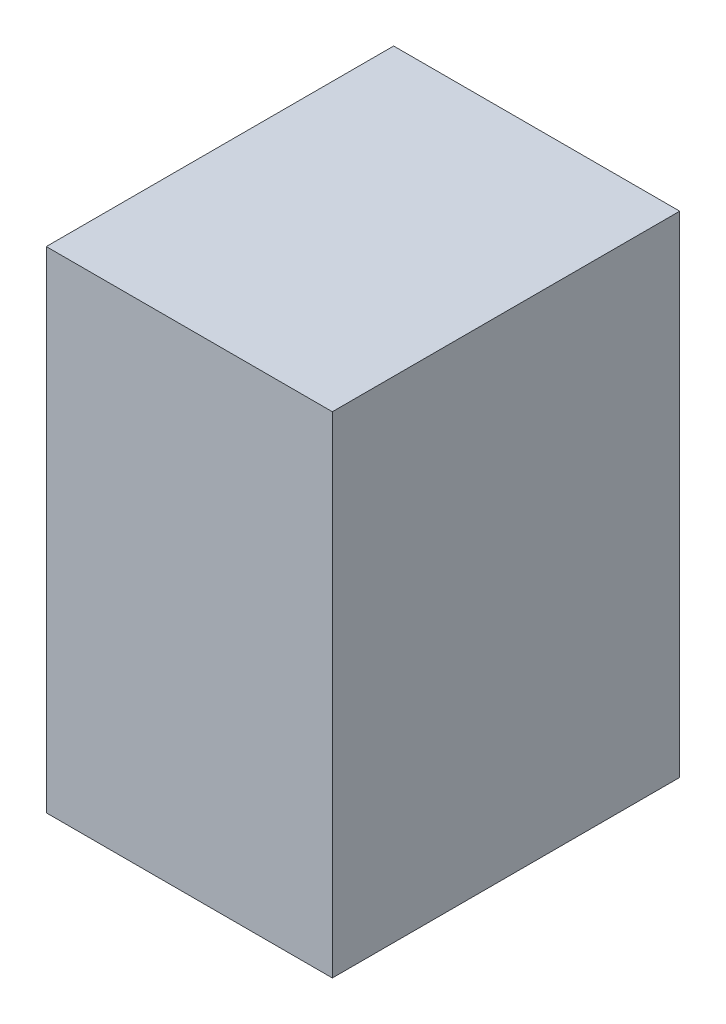
SolidWorks part; units mm, degrees
material "Plain Carbon Steel"
ref_plane "Front Plane" through (0, 0, 0) normal (0, 0, 1) x (1, 0, 0)
ref_plane "Top Plane" through (0, 0, 0) normal (0, 1, 0) x (1, 0, 0)
ref_plane "Right Plane" through (0, 0, 0) normal (1, 0, 0) x (0, 0, -1)
sketch "Sketch1" plane through (0, 0, 0) normal (0, 1, 0) x (1, 0, 0)
  line L1 (-35, -42.5) -> (35, -42.5)
  line L2 (-35, -42.5) -> (-35, 42.5)
  line L3 (-35, 42.5) -> (35, 42.5)
  line L4 (35, -42.5) -> (35, 42.5)
  line L5 (-35, -42.5) -> (35, 42.5) construction
  line L6 (-35, 42.5) -> (35, -42.5) construction
  point P0 (0, 0)
  dimension "D1" = 70
  dimension "D2" = 85
extrude "Boss-Extrude1" add sketch "Sketch1" along normal blind 120
shell "Shell1" thickness 12
